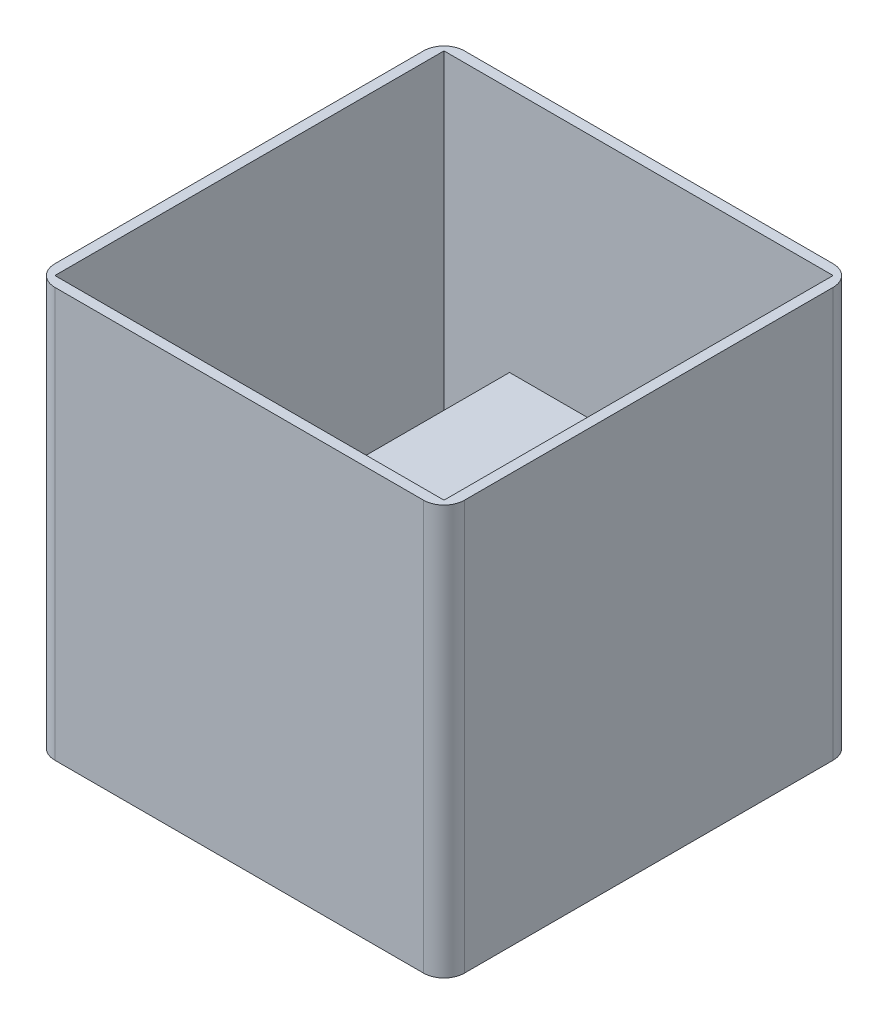
SolidWorks part; units mm, degrees
ref_plane "Front Plane" through (0, 0, 0) normal (0, 0, 1) x (1, 0, 0)
ref_plane "Top Plane" through (0, 0, 0) normal (0, 1, 0) x (1, 0, 0)
ref_plane "Right Plane" through (0, 0, 0) normal (1, 0, 0) x (0, 0, -1)
sketch "Sketch1" plane through (0, 0, 0) normal (0, 1, 0) x (1, 0, 0)
  line L1 (-100, -100) -> (100, -100)
  line L2 (-100, -100) -> (-100, 100)
  line L3 (-100, 100) -> (100, 100)
  line L4 (100, -100) -> (100, 100)
  line L5 (-100, -100) -> (100, 100) construction
  line L6 (-100, 100) -> (100, -100) construction
  point P0 (0, 0)
  dimension "D1" = 200
extrude "Boss-Extrude1" add sketch "Sketch1" against normal blind 200
sketch "Sketch2" plane through (0, 0, 0) normal (0, 1, 0) x (1, 0, 0)
  line L0 (-100, -100) -> (100, -100) construction
  line L4 (-95, -95) -> (95, -95)
  line L5 (-95, -95) -> (-95, 95)
  line L6 (-95, 95) -> (95, 95)
  line L7 (95, -95) -> (95, 95)
  line L8 (-95, -95) -> (95, 95) construction
  line L9 (-95, 95) -> (95, -95) construction
  point P5 (0, 0)
  dimension "D1" = 190
  dimension "D2" = 100
extrude "Cut-Extrude1" cut sketch "Sketch2" against normal blind 120
sketch "Sketch3" plane through (0, -200, 0) normal (0, -1, 0) x (-1, 0, 0)
  line L0 (-100, 100) -> (100, 100) construction
  line L1 (-60, 18.1052) -> (-60, 87)
  line L2 (0, 97) -> (0, -23) construction
  line L7 (50, -23) -> (-50, -23)
  line L8 (60, -13) -> (60, 18.1052)
  line L9 (50, 97) -> (-50, 97)
  line L10 (-60, -13) -> (-60, 18.1052)
  line L11 (60, -23) -> (-60, 97) construction
  line L12 (60, 97) -> (-60, -23) construction
  line L17 (60, 18.1052) -> (60, 87)
  arc A0 (60, 87) -> (50, 97) centre (50, 87) ccw
  arc A1 (-50, 97) -> (-60, 87) centre (-50, 87) ccw
  arc A2 (-50, -23) -> (-60, -13) centre (-50, -13) cw
  arc A3 (50, -23) -> (60, -13) centre (50, -13) ccw
  point P5 (0, 37)
  point P23 (-55.2997, 35.1052)
  point P30 (-60, 42.1052)
  dimension "D3" = 10
  dimension "D1" = 120
  dimension "D2" = 63
extrude "Cut-Extrude2" cut sketch "Sketch3" against normal blind 75
sketch "Sketch4" plane through (0, -125, 0) normal (0, -1, 0) x (-1, 0, 0)
  line L0 (-50, -23) -> (50, -23) construction
  line L1 (0, -23) -> (0, -3) construction
  line L5 (11, -3) -> (-11, -3) construction
  line L6 (11, -3.5) -> (-11, -3.5)
  line L7 (11, -2.5) -> (-11, -2.5)
  arc A0 (11, -3.5) -> (11, -2.5) centre (11, -3) ccw
  arc A1 (-11, -2.5) -> (-11, -3.5) centre (-11, -3) ccw
  point P10 (0, -3)
  dimension "D3" = 0.5
  dimension "D1" = 20
  dimension "D2" = 22
extrude "Cut-Extrude3" cut sketch "Sketch4" against normal blind 320
sketch "Sketch5" plane through (0, -120, 0) normal (0, 1, 0) x (1, 0, 0)
  line L0 (-60, 95) -> (-63, 95) construction
  line L1 (95, 95) -> (-95, 95) construction
  line L2 (-60, -13) -> (-60, 87) construction
  line L3 (-63, 95) -> (-63, -26)
  line L4 (-63, -26) -> (63, -26)
  line L5 (63, -26) -> (63, 95)
  line L6 (60, 87) -> (60, -13) construction
  line L7 (50, -23) -> (-50, -23) construction
  line L8 (-95, 95) -> (-95, -95)
  line L9 (-95, -95) -> (95, -95)
  line L10 (95, -95) -> (95, 95)
  line L11 (-95, 95) -> (-95, -95) construction
  line L12 (95, -95) -> (95, 95) construction
  line L13 (-95, -95) -> (95, -95) construction
  line L14 (-95, 95) -> (-63, 95)
  line L15 (63, 95) -> (95, 95)
  dimension "D1" = 3
  dimension "D2" = 3
  dimension "D3" = 3
  dimension "D4" = 0
  dimension "D5" = 0
  dimension "D6" = 0
extrude "Cut-Extrude4" cut sketch "Sketch5" against normal blind 50
sketch "Sketch6" plane through (0, -200, 0) normal (0, -1, 0) x (1, 0, 0)
  line L0 (-60, -37) -> (-75, -37) construction
  line L1 (-60, 13) -> (-60, -87) construction
  line L2 (0, 23) -> (0, -97) construction
  line L3 (50, 23) -> (-50, 23) construction
  line L4 (-50, -97) -> (50, -97) construction
  line L5 (-60, -37) -> (-75, -37) construction
  line L6 (-70, -44) -> (-75, -44)
  line L7 (-70, -30) -> (-75, -30)
  line L8 (-60, -29.5152) -> (-60, -44) construction
  line L12 (-60, -54) -> (-60, -20)
  line L14 (70, -44) -> (75, -44)
  line L15 (70, -30) -> (75, -30)
  line L16 (60, -54) -> (60, -20)
  arc A3 (-75, -30) -> (-75, -44) centre (-75, -37) ccw
  arc A4 (-60, -20) -> (-70, -30) centre (-70, -20) cw
  arc A5 (-60, -54) -> (-70, -44) centre (-70, -54) ccw
  arc A6 (60, -54) -> (70, -44) centre (70, -54) cw
  arc A7 (75, -30) -> (75, -44) centre (75, -37) cw
  arc A8 (60, -20) -> (70, -30) centre (70, -20) ccw
  point P14 (-60, -37)
  dimension "D3" = 10
  dimension "D4" = 10
  dimension "D5" = 7
extrude "Cut-Extrude5" cut sketch "Sketch6" against normal blind 10
sketch "Croquis1" plane through (0, -190, 0) normal (0, -1, 0) x (1, 0, 0)
  line L0 (0, 23) -> (0, -97) construction
  line L1 (50, 23) -> (-50, 23) construction
  line L2 (-50, -97) -> (50, -97) construction
  line L3 (0, -37) -> (-75, -37) construction
  line L4 (-60, 13) -> (-60, -20) construction
  circle A0 centre (-75, -37) radius 2.5
  circle A1 centre (75, -37) radius 2.5
  dimension "D1" = 5
  dimension "D2" = 15
extrude "Cortar-Extruir1" cut sketch "Croquis1" against normal blind 15
fillet "Redondeo1" radius 10 4 edges at (-100, -100, -100) (-100, -100, 100) (100, -100, -100) (100, -100, 100)
